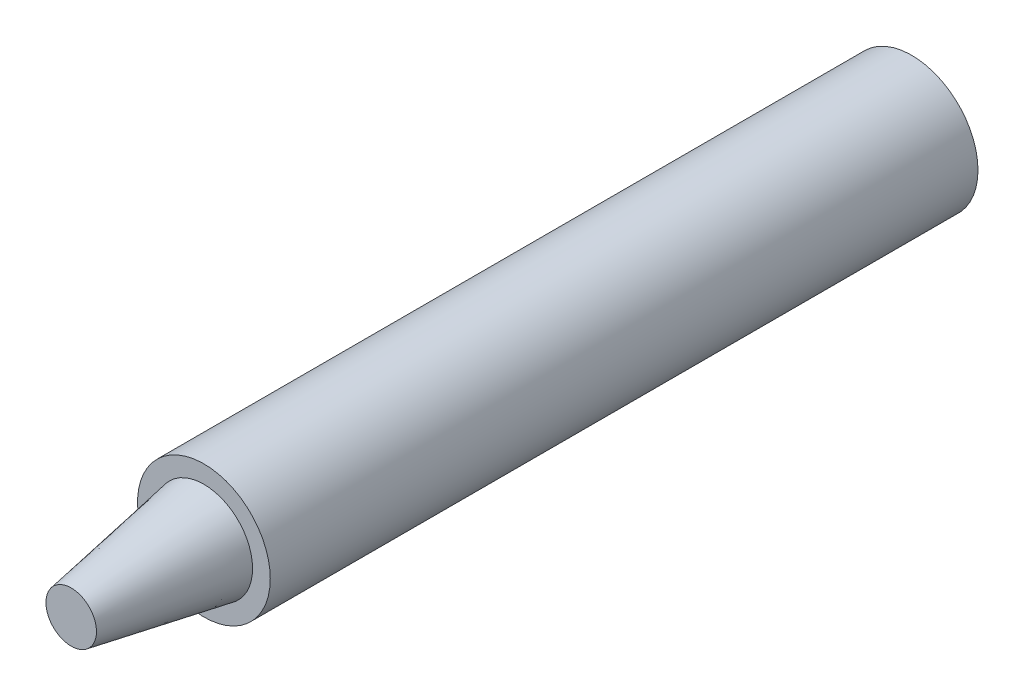
SolidWorks part; units mm, degrees
ref_plane "Plane1" through (0, 0, 0) normal (0, 0, 1) x (1, 0, 0)
ref_plane "Plane2" through (0, 0, 0) normal (0, 1, 0) x (1, 0, 0)
ref_plane "Plane3" through (0, 0, 0) normal (1, 0, 0) x (0, 0, -1)
other "Configuration Table"
sketch "Sketch1" plane through (0, 0, 0) normal (0, 0, 1) x (1, 0, 0)
  circle A0 centre (0, 0) radius 9.525
  dimension "D1" = 19.05
extrude "Base-Extrude" add sketch "Sketch1" along normal blind 101.6
sketch "Sketch2" plane through (0, 0, 101.6) normal (0, 0, 1) x (1, 0, 0)
  circle A3 centre (0, 0) radius 6.985
  circle A4 centre (0, 0) radius 6.985
  dimension "D2" = 2.54
extrude "Boss-Extrude1" add sketch "Sketch2" along normal blind 19.05 draft 10
